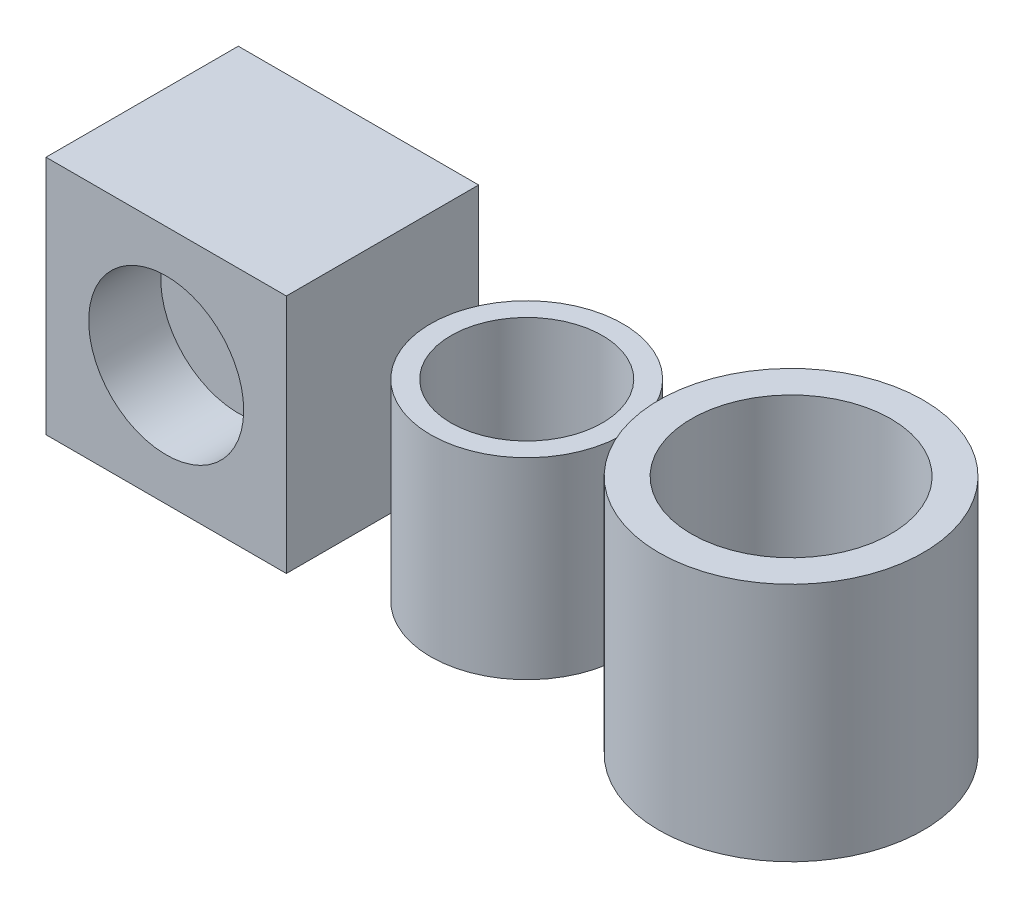
SolidWorks part; units mm, degrees
ref_plane "Front Plane" through (0, 0, 0) normal (0, 0, 1) x (1, 0, 0)
ref_plane "Top Plane" through (0, 0, 0) normal (0, 1, 0) x (1, 0, 0)
ref_plane "Right Plane" through (0, 0, 0) normal (1, 0, 0) x (0, 0, -1)
sketch "Sketch1" plane through (0, 0, 0) normal (0, 1, 0) x (1, 0, 0)
  circle A0 centre (0, 0) radius 4
  circle A1 centre (0, 0) radius 3.15
  dimension "D1" = 8
  dimension "D2" = 6.3
extrude "Boss-Extrude1" add sketch "Sketch1" along normal blind 8
sketch "Sketch2" plane through (0, 0, 0) normal (0, 1, 0) x (1, 0, 0)
  circle A0 centre (11, 0) radius 4.15
  circle A1 centre (11, 0) radius 5.5
  dimension "D1" = 8.3
  dimension "D2" = 11
  dimension "D3" = 11
extrude "Boss-Extrude2" add sketch "Sketch2" along normal blind 10 separate body
sketch "Sketch3" plane through (0, 0, 0) normal (0, 0, 1) x (1, 0, 0)
  line L0 (-4, 0) -> (4, 0) construction
  line L1 (-16, 10) -> (-6, 10)
  line L2 (-16, 10) -> (-16, 0)
  line L3 (-16, 0) -> (-6, 0)
  line L4 (-6, 10) -> (-6, 0)
  dimension "D1" = 10
  dimension "D2" = 10
  dimension "D3" = 6
extrude "Boss-Extrude3" add sketch "Sketch3" along normal mid plane 8 separate body
sketch "Sketch4" plane through (0, 0, 4) normal (0, 0, 1) x (1, 0, 0)
  line L0 (-16, 5) -> (-6, 5) construction
  line L1 (-16, 10) -> (-16, 0) construction
  line L2 (-6, 0) -> (-6, 10) construction
  circle A0 centre (-11, 5) radius 3.225
  dimension "D1" = 6.45
extrude "Cut-Extrude1" cut sketch "Sketch4" against normal blind 3
